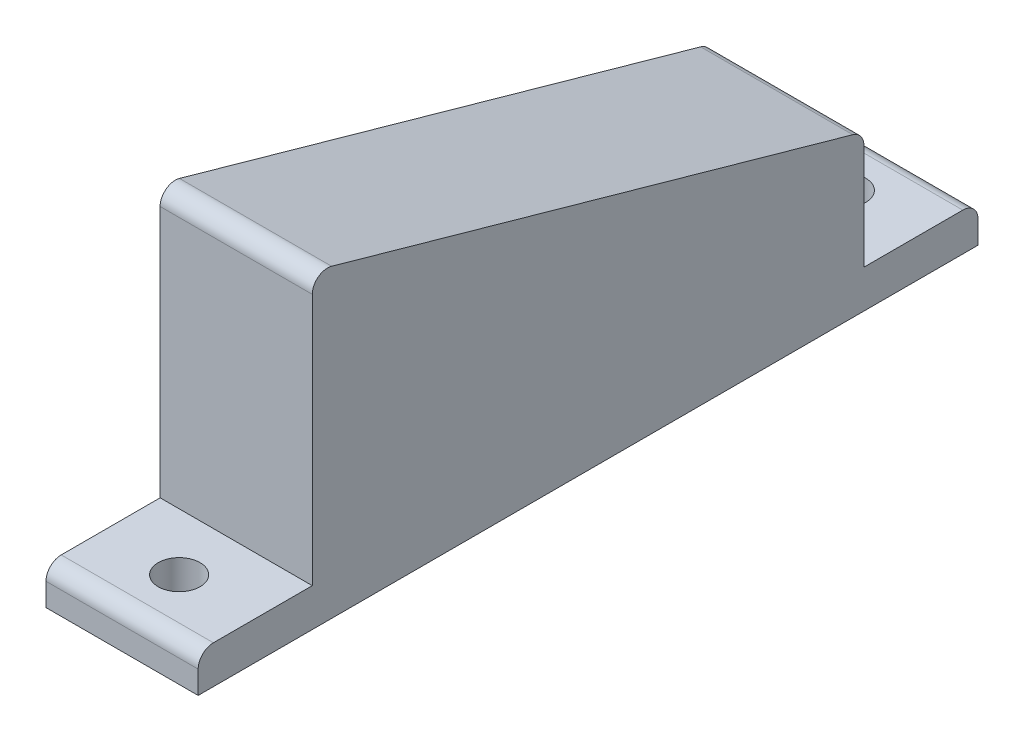
SolidWorks part; units mm, degrees
ref_plane "前视基准面" through (0, 0, 0) normal (0, 0, 1) x (1, 0, 0)
ref_plane "上视基准面" through (0, 0, 0) normal (0, 1, 0) x (1, 0, 0)
ref_plane "右视基准面" through (0, 0, 0) normal (1, 0, 0) x (0, 0, -1)
other "Configuration Table"
sketch "草图1" plane through (0, 0, 0) normal (1, 0, 0) x (0, 0, -1)
  line L0 (-38.3868, 40.8) -> (-38.3868, 0)
  line L1 (-38.3868, 0) -> (34.1132, 0)
  line L2 (34.1132, 0) -> (34.1132, 20.4)
  line L3 (-38.3868, 40.8) -> (34.1132, 20.4)
  dimension "D1" = 20.4
  dimension "D2" = 40.8
  dimension "D3" = 72.5
extrude "凸台-拉伸1" add sketch "草图1" along normal blind 20
sketch "草图2" plane through (0, 0, 0) normal (0, -1, 0) x (1, 0, 0)
  line L0 (20, 2.1368) -> (43.119, 2.1368) construction
  line L1 (0, 38.3868) -> (20, 38.3868)
  line L2 (0, 38.3868) -> (0, 53.3868)
  line L3 (0, 53.3868) -> (20, 53.3868)
  line L4 (20, 38.3868) -> (20, 53.3868)
  line L5 (20, -34.1132) -> (0, -34.1132)
  line L6 (20, -34.1132) -> (20, -49.1132)
  line L7 (20, -49.1132) -> (0, -49.1132)
  line L8 (0, -34.1132) -> (0, -49.1132)
  line L9 (20, 38.3868) -> (20, -34.1132) construction
  circle A0 centre (10, -41.6132) radius 2.75
  circle A1 centre (10, 45.8868) radius 2.75
  dimension "D3" = 5.5
  dimension "D1" = 15
  dimension "D2" = 15
extrude "凸台-拉伸2" add sketch "草图2" against normal blind 5
fillet "圆角1" radius 2 4 edges at (10, 5, 53.3868) (10, 5, -49.1132) (10, 40.8, 38.3868) (10, 20.4, -34.1132)
